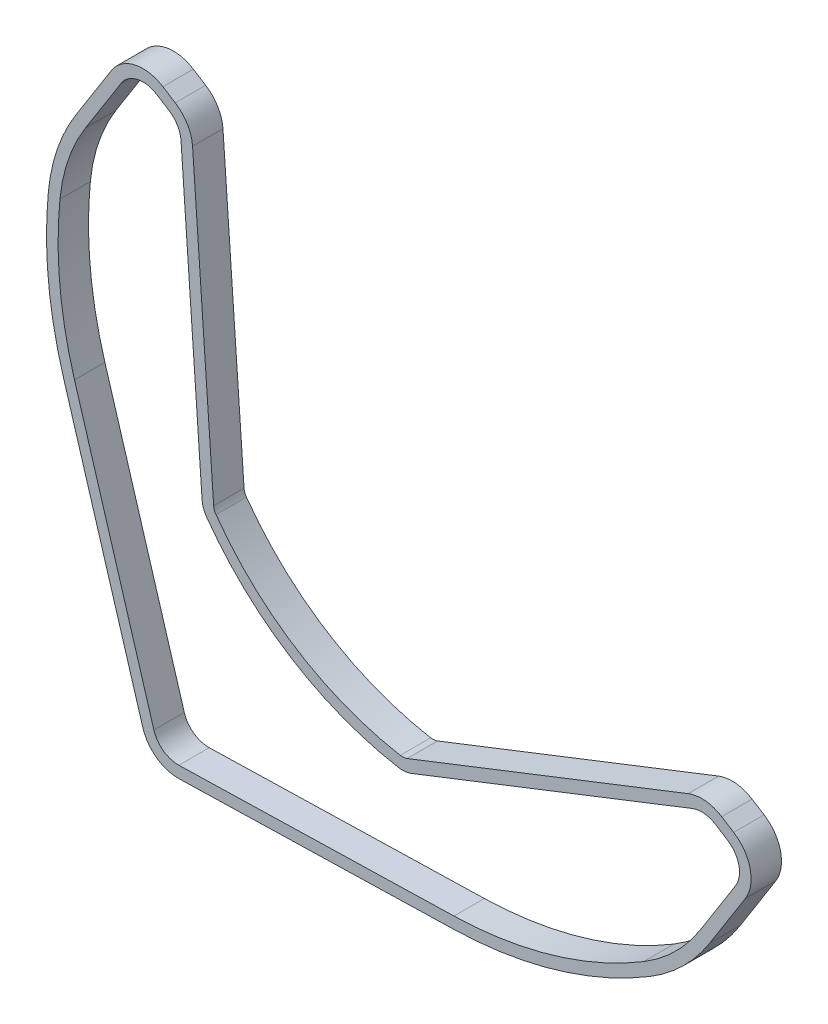
SolidWorks part; units mm, degrees
material "6061-T6 (SS)"
ref_plane "Front Plane" through (0, 0, 0) normal (0, 0, 1) x (1, 0, 0)
ref_plane "Top Plane" through (0, 0, 0) normal (0, 1, 0) x (1, 0, 0)
ref_plane "Right Plane" through (0, 0, 0) normal (1, 0, 0) x (0, 0, -1)
sketch "Sketch1" plane through (0, 0, 0) normal (0, 0, 1) x (1, 0, 0)
  line L0 (-183.3012, -144.9228) -> (-186.8268, -150.507) construction
  line L1 (-176.2613, -146.7901) -> (-174.1789, -176.4657)
  line L2 (-122.6812, -183.1954) -> (-126.2067, -188.7795) construction
  line L3 (-127.3592, -177.661) -> (-155.0828, -188.5232)
  line L4 (-123.4729, -179.6916) -> (-124.6597, -178.9424) construction
  line L5 (-179.4924, -143.6478) -> (-178.2742, -144.4169) construction
  line L6 (-183.7845, -144.6177) -> (-187.31, -150.2019) construction
  line L7 (-179.7974, -144.1311) -> (-178.5793, -144.9002) construction
  line L8 (-122.1979, -183.5005) -> (-125.7235, -189.0846) construction
  line L9 (-123.1678, -179.2084) -> (-124.3546, -178.4591) construction
  line L10 (-176.8314, -146.8301) -> (-174.749, -176.5057) construction
  line L11 (-127.1507, -178.1931) -> (-154.8743, -189.0553) construction
  line L12 (-180.6249, -198.7456) -> (-188.459, -172.7459) construction
  line L13 (-150.4526, -200.2483) -> (-177.5982, -200.9359) construction
  line L14 (-122.8627, -178.7251) -> (-124.0495, -177.9759)
  line L15 (-121.7147, -183.8056) -> (-125.2402, -189.3897)
  line L16 (-150.4381, -200.8196) -> (-177.5837, -201.5072)
  line L17 (-181.1721, -198.9105) -> (-189.0062, -172.9108)
  line L18 (-184.2677, -144.3126) -> (-187.7933, -149.8968)
  line L19 (-179.1873, -143.1646) -> (-177.9691, -143.9337)
  line L20 (-177.4015, -146.8701) -> (-175.3191, -176.5457)
  line L21 (-126.9423, -178.7252) -> (-154.6658, -189.5875)
  line L22 (-123.4729, -179.6916) -> (-124.6597, -178.9424)
  line L23 (-122.6812, -183.1954) -> (-126.2067, -188.7795)
  line L24 (-150.467, -199.677) -> (-177.6126, -200.3646)
  line L25 (-180.0777, -198.5807) -> (-187.9118, -172.581)
  line L26 (-183.3012, -144.9228) -> (-186.8268, -150.507)
  line L27 (-179.7974, -144.1311) -> (-178.5793, -144.9002)
  arc A0 (-180.6249, -198.7456) -> (-177.5982, -200.9359) centre (-177.6761, -197.8571) ccw construction
  arc A1 (-173.9467, -177.1132) -> (-155.766, -188.5916) centre (-150.8579, -160.6801) ccw construction
  arc A2 (-128.0308, -179.544) -> (-124.6597, -178.9424) centre (-126.0156, -181.0901) cw construction
  arc A3 (-188.459, -172.7459) -> (-189.9166, -157.7937) centre (-151.4318, -161.5892) cw construction
  arc A4 (-189.3478, -157.8498) -> (-186.8268, -150.507) centre (-172.5768, -159.5038) cw construction
  arc A5 (-131.752, -194.213) -> (-126.2067, -188.7795) centre (-140.4568, -179.7828) ccw construction
  arc A6 (-123.4729, -179.6916) -> (-122.6812, -183.1954) centre (-124.8289, -181.8394) cw construction
  arc A7 (-183.3012, -144.9228) -> (-179.7974, -144.1311) centre (-181.1534, -146.2788) cw construction
  arc A8 (-177.8917, -148.5564) -> (-179.8353, -153.638) centre (-151.4318, -161.5892) ccw construction
  arc A9 (-178.5793, -144.9002) -> (-177.8917, -148.5564) centre (-179.9353, -147.0479) cw construction
  arc A10 (-173.9467, -177.1132) -> (-174.1789, -176.4657) centre (-172.912, -176.3768) cw
  arc A11 (-173.9467, -177.1132) -> (-174.1058, -175.9434) centre (-172.912, -176.3768) cw construction
  arc A12 (-154.6415, -188.2322) -> (-155.766, -188.5916) centre (-155.5461, -187.3408) cw construction
  arc A13 (-154.8743, -189.0553) -> (-155.865, -189.1544) centre (-155.5461, -187.3408) cw construction
  arc A14 (-174.4123, -177.4446) -> (-155.865, -189.1544) centre (-150.8579, -160.6801) ccw construction
  arc A15 (-174.4123, -177.4446) -> (-174.749, -176.5057) centre (-172.912, -176.3768) cw construction
  arc A16 (-178.2742, -144.4169) -> (-176.8314, -146.8301) centre (-179.9353, -147.0479) cw construction
  arc A17 (-183.7845, -144.6177) -> (-179.4924, -143.6478) centre (-181.1534, -146.2788) cw construction
  arc A18 (-189.9166, -157.7937) -> (-187.31, -150.2019) centre (-172.5768, -159.5038) cw construction
  arc A19 (-131.4568, -194.7024) -> (-150.4526, -200.2483) centre (-151.4318, -161.5892) cw construction
  arc A20 (-131.4568, -194.7024) -> (-125.7235, -189.0846) centre (-140.4568, -179.7828) ccw construction
  arc A21 (-123.1678, -179.2084) -> (-122.1979, -183.5005) centre (-124.8289, -181.8394) cw construction
  arc A22 (-127.1507, -178.1931) -> (-124.3546, -178.4591) centre (-126.0156, -181.0901) cw construction
  arc A23 (-173.9467, -177.1132) -> (-155.766, -188.5916) centre (-150.8579, -160.6801) ccw
  arc A24 (-155.0828, -188.5232) -> (-155.766, -188.5916) centre (-155.5461, -187.3408) cw
  arc A25 (-127.3592, -177.661) -> (-124.0495, -177.9759) centre (-126.0156, -181.0901) cw
  arc A26 (-122.8627, -178.7251) -> (-121.7147, -183.8056) centre (-124.8289, -181.8394) cw
  arc A27 (-131.1616, -195.1917) -> (-125.2402, -189.3897) centre (-140.4568, -179.7828) ccw
  arc A28 (-131.1616, -195.1917) -> (-150.4381, -200.8196) centre (-151.4318, -161.5892) cw
  arc A29 (-181.1721, -198.9105) -> (-177.5837, -201.5072) centre (-177.6761, -197.8571) ccw
  arc A30 (-189.0062, -172.9108) -> (-190.4853, -157.7376) centre (-151.4318, -161.5892) cw
  arc A31 (-190.4853, -157.7376) -> (-187.7933, -149.8968) centre (-172.5768, -159.5038) cw
  arc A32 (-184.2677, -144.3126) -> (-179.1873, -143.1646) centre (-181.1534, -146.2788) cw
  arc A33 (-177.9691, -143.9337) -> (-176.2613, -146.7901) centre (-179.9353, -147.0479) cw
  arc A34 (-174.8779, -177.776) -> (-175.3191, -176.5457) centre (-172.912, -176.3768) cw
  arc A35 (-174.8779, -177.776) -> (-155.964, -189.7173) centre (-150.8579, -160.6801) ccw
  arc A36 (-154.6658, -189.5875) -> (-155.964, -189.7173) centre (-155.5461, -187.3408) cw
  arc A37 (-126.9423, -178.7252) -> (-124.6597, -178.9424) centre (-126.0156, -181.0901) cw
  arc A38 (-123.4729, -179.6916) -> (-122.6812, -183.1954) centre (-124.8289, -181.8394) cw
  arc A39 (-131.752, -194.213) -> (-126.2067, -188.7795) centre (-140.4568, -179.7828) ccw
  arc A40 (-131.752, -194.213) -> (-150.467, -199.677) centre (-151.4318, -161.5892) cw
  arc A41 (-180.0777, -198.5807) -> (-177.6126, -200.3646) centre (-177.6761, -197.8571) ccw
  arc A42 (-187.9118, -172.581) -> (-189.3478, -157.8498) centre (-151.4318, -161.5892) cw
  arc A43 (-189.3478, -157.8498) -> (-186.8268, -150.507) centre (-172.5768, -159.5038) cw
  arc A44 (-183.3012, -144.9228) -> (-179.7974, -144.1311) centre (-181.1534, -146.2788) cw
  arc A45 (-178.5793, -144.9002) -> (-177.4015, -146.8701) centre (-179.9353, -147.0479) cw
  point P19 (-174.2732, -176.6445)
  point P21 (-155.2024, -188.6848)
  point P36 (-174.2732, -176.6445)
  dimension "D1" = 225.3513
  dimension "D2" = 0.5715
  dimension "D3" = 0.5715
extrude "Boss-Extrude1" add sketch "Sketch1" along normal blind 3
